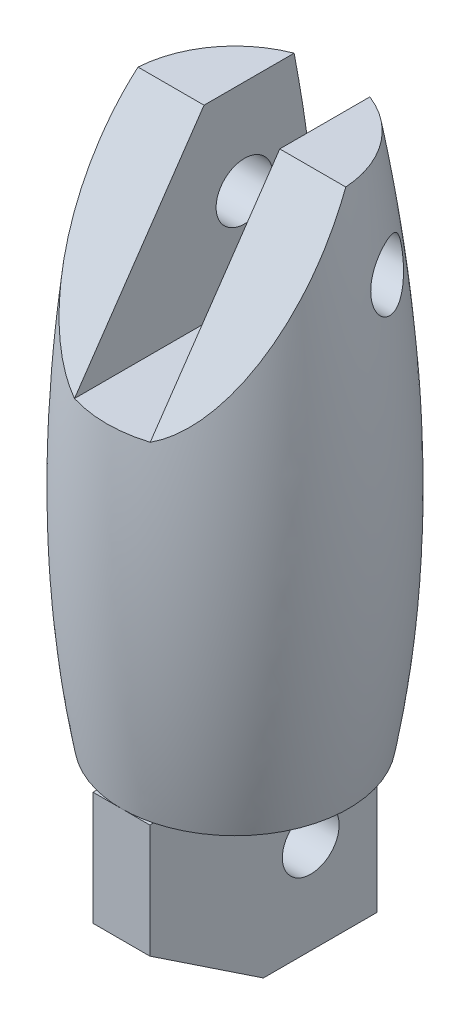
SolidWorks part; units mm, degrees
ref_plane "Front Plane" through (0, 0, 0) normal (0, 0, 1) x (1, 0, 0)
ref_plane "Top Plane" through (0, 0, 0) normal (0, 1, 0) x (1, 0, 0)
ref_plane "Right Plane" through (0, 0, 0) normal (1, 0, 0) x (0, 0, -1)
sketch "Sketch1" plane through (0, 0, 0) normal (1, 0, 0) x (0, 0, -1)
  line L0 (0, 0) -> (0, 28)
  line L1 (0, 0) -> (6, 0)
  line L2 (0, 28) -> (5.5, 28)
  line L3 (11.0567, -3.5138) -> (-0.0567, 59.5138) construction
  spline S0 degree 2 poles (5.5, 28) (8.2784, 12.2431) (6, 0) knots 0 0 0 1 1 1
  dimension "D4" = 100
  dimension "D1" = 28
  dimension "D2" = 5.5
  dimension "D3" = 6
revolve "Revolve1" add sketch "Sketch1" angle 360 about L0
sketch "Sketch3" plane through (0, 0, 0) normal (0, 0, 1) x (1, 0, 0)
  line L0 (5.5, 28) -> (-5.5, 28) construction
  line L1 (-2, 28) -> (2, 28)
  line L2 (-2, 28) -> (-2, 18)
  line L3 (-2, 18) -> (2, 18)
  line L4 (2, 28) -> (2, 18)
  line L10 (0, 28) -> (0, 18) construction
  dimension "D1" = 10
  dimension "D2" = 4
extrude "Cut-Extrude2" cut sketch "Sketch3" against normal mid plane 23
sketch "Sketch4" plane through (0, 0, 0) normal (1, 0, 0) x (0, 0, -1)
  line L0 (-6.4801, 18) -> (0.3634, 28)
  line L2 (5.1235, 28) -> (-5.1235, 28) construction
  line L4 (0.3634, 28) -> (-6.7818, 28)
  line L5 (-6.7818, 28) -> (-6.4801, 18)
extrude "Cut-Extrude3" cut sketch "Sketch4" against normal through all and the other way through all
sketch "Sketch6" plane through (0, 0, 0) normal (1, 0, 0) x (0, 0, -1)
  line L0 (-6, 0) -> (-6, -6)
  line L1 (-6, 0) -> (6, 0) construction
  line L2 (-6, 0) -> (6, 0)
  line L3 (6, 0) -> (6, -10)
  line L5 (-6, -6) -> (0, -10)
  line L6 (0, -10) -> (6, -10)
  dimension "D1" = 6
  dimension "D2" = 10
  dimension "D3" = 6
extrude "Boss-Extrude1" add sketch "Sketch6" along normal mid plane 3
sketch "Sketch5" plane through (0, 0, 0) normal (1, 0, 0) x (0, 0, -1)
  line L0 (0, -10) -> (6, -10) construction
  line L1 (5.1235, 28) -> (0.3634, 28) construction
  circle A0 centre (2.5, 23) radius 1.5
  circle A1 centre (2.5, -5) radius 1.5
  dimension "D1" = 3
  dimension "D2" = 5
  dimension "D3" = 5
  dimension "D4" = 2.5
extrude "Cut-Extrude4" cut sketch "Sketch5" against normal through all and the other way through all
